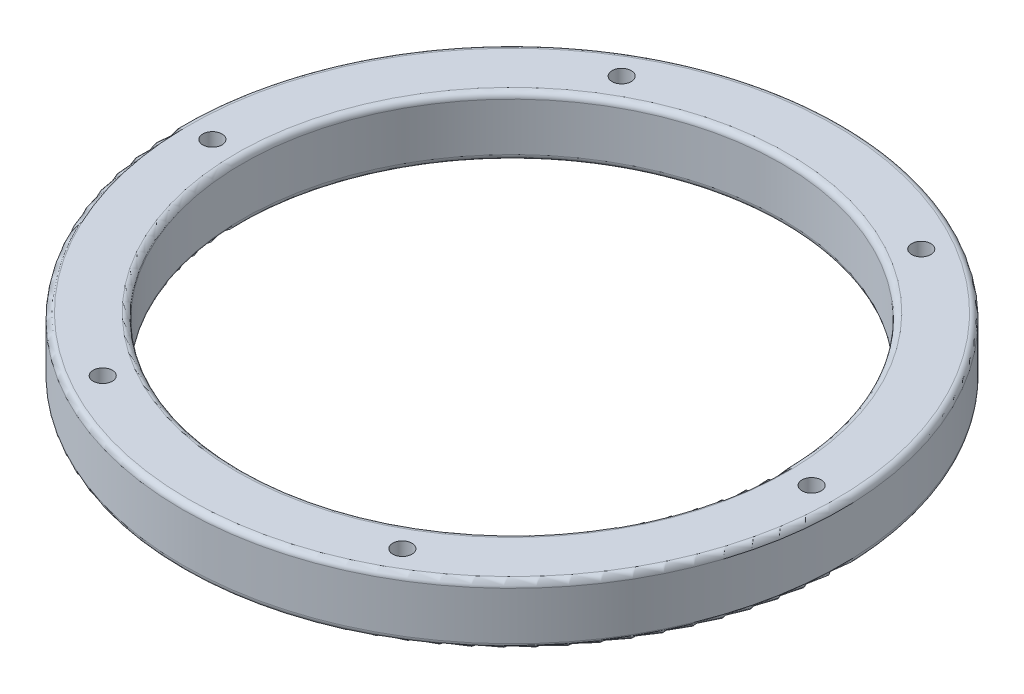
SolidWorks part; units mm, degrees
ref_plane "前视基准面" through (0, 0, 0) normal (0, 0, 1) x (1, 0, 0)
ref_plane "上视基准面" through (0, 0, 0) normal (0, 1, 0) x (1, 0, 0)
ref_plane "右视基准面" through (0, 0, 0) normal (1, 0, 0) x (0, 0, -1)
sketch "草图1" plane through (0, 0, 0) normal (0, 1, 0) x (1, 0, 0)
  circle A0 centre (0, 0) radius 45
  circle A1 centre (0, 0) radius 55
  circle A2 centre (50, 0) radius 1.6
  circle A3 centre (25, -43.3013) radius 1.6
  circle A4 centre (-25, -43.3013) radius 1.6
  circle A5 centre (-50, 0) radius 1.6
  circle A6 centre (-25, 43.3013) radius 1.6
  circle A7 centre (25, 43.3013) radius 1.6
  point P18 (0, 0)
  dimension "D1" = 90
  dimension "D2" = 110
  dimension "D3" = 3.2
  dimension "D5" = 6
  dimension "D4" = 50
extrude "凸台-拉伸1" add sketch "草图1" along normal blind 10
fillet "圆角1" radius 1 4 edges at (0, 0, 55) (0, 10, 55) (0, 0, 45) (0, 10, 45)
